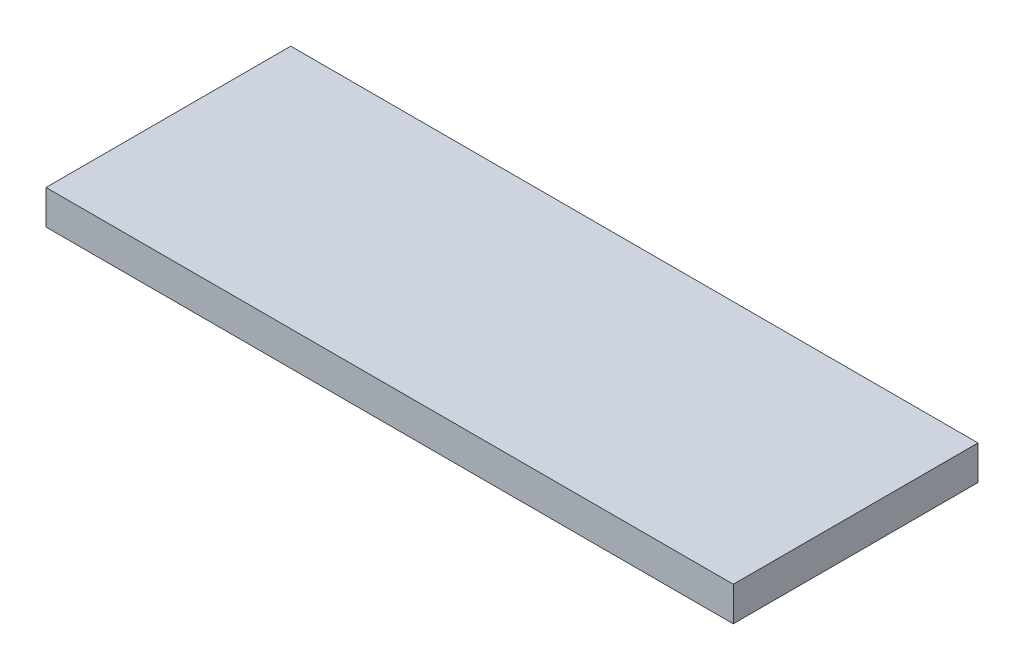
SolidWorks part; units mm, degrees
ref_plane "Front Plane" through (0, 0, 0) normal (0, 0, 1) x (1, 0, 0)
ref_plane "Top Plane" through (0, 0, 0) normal (0, 1, 0) x (1, 0, 0)
ref_plane "Right Plane" through (0, 0, 0) normal (1, 0, 0) x (0, 0, -1)
sketch "Sketch1" plane through (0, 0, 0) normal (0, 1, 0) x (1, 0, 0)
  line L1 (101.8093, -36.2531) -> (-101.8093, -36.2531)
  line L2 (101.8093, -36.2531) -> (101.8093, 36.2531)
  line L3 (101.8093, 36.2531) -> (-101.8093, 36.2531)
  line L4 (-101.8093, -36.2531) -> (-101.8093, 36.2531)
  line L5 (101.8093, -36.2531) -> (-101.8093, 36.2531) construction
  line L6 (101.8093, 36.2531) -> (-101.8093, -36.2531) construction
  point P0 (0, 0)
extrude "Boss-Extrude1" add sketch "Sketch1" along normal blind 10.16
